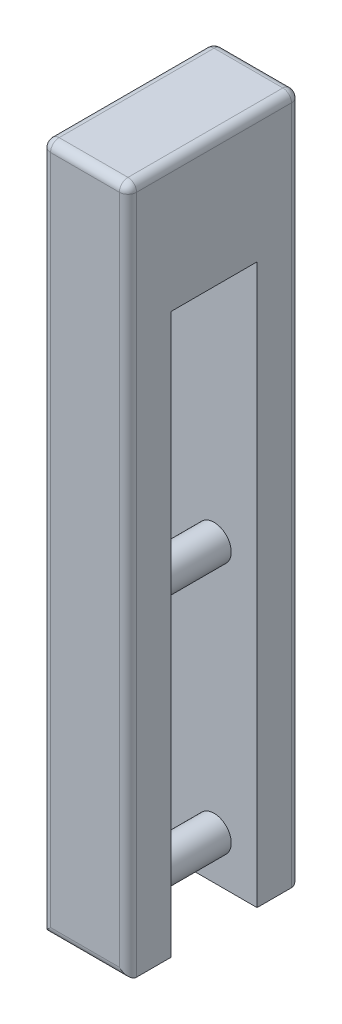
SolidWorks part; units mm, degrees
ref_plane "Front Plane" through (0, 0, 0) normal (0, 0, 1) x (1, 0, 0)
ref_plane "Top Plane" through (0, 0, 0) normal (0, 1, 0) x (1, 0, 0)
ref_plane "Right Plane" through (0, 0, 0) normal (1, 0, 0) x (0, 0, -1)
sketch "Sketch1" plane through (0, 0, 0) normal (0, 0, 1) x (1, 0, 0)
  line L1 (0, 0) -> (10, 0)
  line L2 (0, 0) -> (0, 80)
  line L3 (0, 80) -> (10, 80)
  line L4 (10, 0) -> (10, 80)
  dimension "D1" = 80
  dimension "D2" = 10
extrude "Boss-Extrude1" add sketch "Sketch1" along normal blind 5
sketch "Sketch2" plane through (0, 0, 5) normal (0, 0, 1) x (1, 0, 0)
  line L0 (10, 0) -> (10, 80) construction
  line L1 (0, 0) -> (10, 0) construction
  circle A0 centre (5, 5) radius 2
  circle A1 centre (5, 34.2857) radius 2
  point P8 (0, 0)
  dimension "D1" = 5
  dimension "D2" = 4
  dimension "D5" = 4
  dimension "D3" = 5
  dimension "D4" = 5
  dimension "D6" = 34.2857
extrude "Boss-Extrude2" add sketch "Sketch2" along normal blind 5
mirror "Mirror2" about plane through (5, 34.2857, 10) normal (0, 0, 1) of "Boss-Extrude1", "Boss-Extrude2"
sketch "Sketch3" plane through (0, 0, 5) normal (0, 0, 1) x (1, 0, 0)
  line L0 (10, 0) -> (10, 80) construction
  line L1 (0, 80) -> (10, 80)
  line L2 (0, 80) -> (0, 65)
  line L3 (0, 65) -> (10, 65)
  line L4 (10, 80) -> (10, 65)
  dimension "D1" = 15
extrude "Boss-Extrude4" add sketch "Sketch3" along normal blind 10 contours L3 L4 L1 L2
fillet "Fillet1" radius 1 10 edges at (0, 40, 20) (10, 40, 20) (5, 0, 20) (10, 80, 10) (5, 80, 20) (0, 80, 10) (5, 0, 0) (10, 40, 0) (5, 80, 0) (0, 40, 0)
equation "\"claw_length\"= 80"
equation "\"D1@Sketch1\"=\"claw_length\""
equation "\"claw_width\"=10"
equation "\"D2@Sketch1\"=\"claw_width\""
equation "\"claw_thickness\"=5"
equation "\"D1@Boss-Extrude1\"=\"claw_thickness\""
equation "\"D1@Sketch2\"= \"claw_width\"/2"
equation "\"pin_d\"= 4"
equation "\"D2@Sketch2\"=\"pin_d\""
equation "\"dist_pin_edge\"=5"
equation "\"D3@Sketch2\"=\"dist_pin_edge\""
equation "\"D4@Sketch2\"= \"claw_width\"/2"
equation "\"D5@Sketch2\"= \"pin_d\""
equation "\"D6@Sketch2\"=\"claw_length\"*3/7"
equation "\"D1@Boss-Extrude2\"= \"claw_width\"/2"
equation "\"claw_end_length\"=15"
equation "\"D1@Sketch3\"=\"claw_end_length\""
equation "\"D1@Boss-Extrude4\"= \"claw_thickness\"*2"
equation "\"fillet_size\"=1"
equation "\"D1@Fillet1\"=\"fillet_size\""
